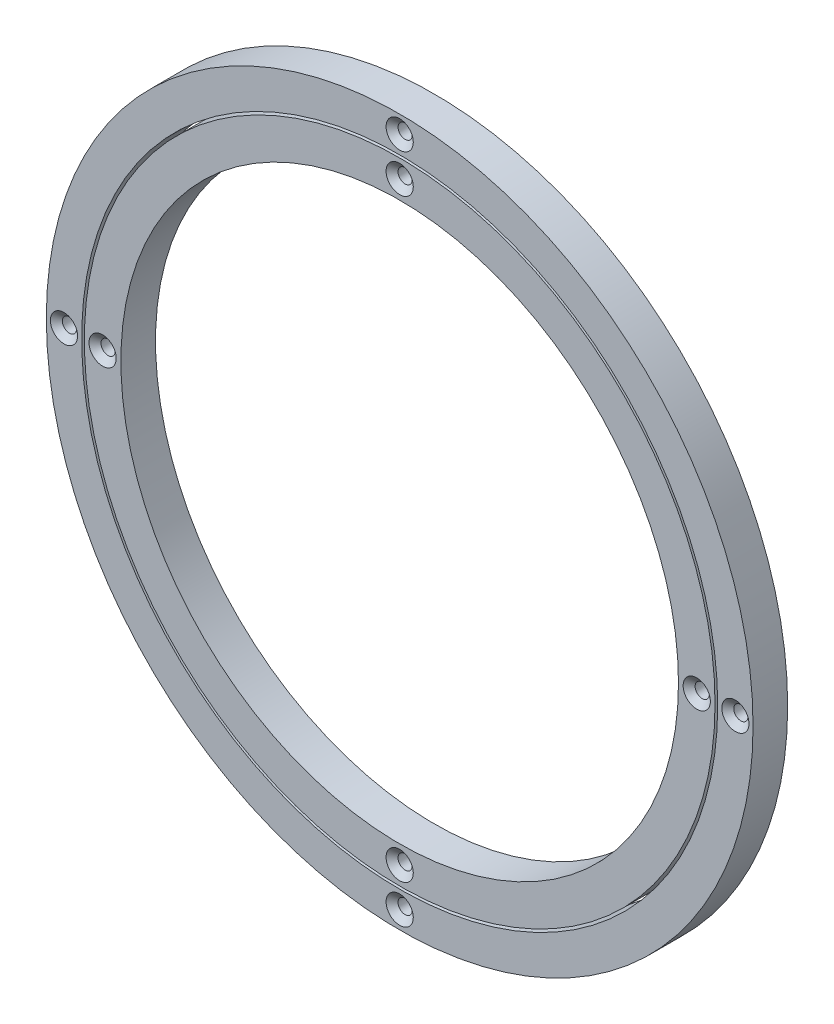
SolidWorks part; units mm, degrees
ref_plane "Front" through (0, 0, 0) normal (0, 0, 1) x (1, 0, 0)
ref_plane "Top" through (0, 0, 0) normal (0, 1, 0) x (1, 0, 0)
ref_plane "Right" through (0, 0, 0) normal (1, 0, 0) x (0, 0, -1)
sketch "Sketch1" plane through (0, 0, 0) normal (0, 0, 1) x (1, 0, 0)
  circle A0 centre (0, 0) radius 127
  circle A1 centre (0, 0) radius 114.3
  circle A2 centre (0, 0) radius 113.3348
  circle A3 centre (0, 0) radius 100.203
  dimension "D1" = 254
  dimension "D2" = 12.7
  dimension "D3" = 0.9652
  dimension "D4" = 13.1318
extrude "Boss-Extrude1" add sketch "Sketch1" along normal blind 12.446 contours A2 A3 | A0 A1
hole_wizard "CSK for #10 Flat Head Machine Screw (100)2" positions "Sketch10" profile "Sketch11" countersink size "#10" standard "ANSI Inch" end condition through all
sketch "Sketch10" plane through (0, 0, 12.446) normal (0, 0, 1) x (1, 0, 0)
  line L0 (0, -127) -> (0, -114.3) construction
  circle A0 centre (0, 0) radius 120.65 construction
  circle A1 centre (0, 0) radius 127 construction
  circle A2 centre (0, 0) radius 114.3 construction
  point P0 (0, -120.65)
  point P5 (-120.65, 0)
  point P7 (0, 120.65)
  point P9 (120.65, 0)
  point P23 (-7.6226, -121.0991)
  point P24 (0, -120.65)
  point P25 (0, 0)
  point P27 (0, -120.65)
  point P28 (0, 0)
  point P29 (0, 0)
  point P30 (0, 0)
  point P31 (0, 0)
  point P32 (0, 0)
  point P33 (0, 0)
  point P34 (120.65, 0)
  point P35 (0, 120.65)
  point P36 (-120.65, 0)
sketch "Sketch11" plane through (0, -120.65, 12.446) normal (1, 0, 0) x (0, -1, 0)
  line L0 (0, 0) -> (0, 12.446)
  line L1 (0, 12.446) -> (2.5527, 12.446)
  line L2 (2.5527, 12.446) -> (2.5527, 1.9608)
  line L3 (2.5527, 1.9608) -> (4.8895, 0)
  line L5 (4.8895, 0) -> (0, 0)
  line L6 (-2.5527, 1.9608) -> (-4.8895, 0) construction
  line L11 (0, -6.35) -> (0, 107.95) construction
  dimension "Thru Hole Dia." = 5.1054
  dimension "Thru Hole Depth" = 12.446
  dimension "Near C'Sink Dia." = 9.779
  dimension "Near C'Sink Angle" = 100
hole_wizard "CSK for #10 Flat Head Machine Screw (100)4" positions "Sketch14" profile "Sketch15" countersink size "#10" standard "ANSI Inch" end condition through all
sketch "Sketch14" plane through (0, 0, 12.446) normal (0, 0, 1) x (1, 0, 0)
  line L0 (-113.3348, 0) -> (-100.203, 0)
  circle A0 centre (0, 0) radius 113.3348 construction
  circle A1 centre (0, 0) radius 100.203 construction
  circle A3 centre (0, 0) radius 106.7689
  point P0 (0, -106.7689)
  point P2 (-106.7689, 0)
  point P4 (0, 106.7689)
  point P6 (106.7689, 0)
  point P8 (-106.7689, 0)
  point P10 (-106.7689, 0)
  point P29 (-106.7689, 0)
  point P30 (-48.7464, 4.8773)
  point P31 (-106.7689, 0)
  point P32 (0, 0)
  point P33 (0, 106.7689)
  point P34 (0, 0)
  point P35 (106.7689, 0)
  point P36 (0, -106.7208)
  point P37 (0, 0)
  point P38 (0, 0)
  point P39 (0, -106.7689)
sketch "Sketch15" plane through (0, -106.7689, 12.446) normal (1, 0, 0) x (0, -1, 0)
  line L0 (0, 0) -> (0, 12.446)
  line L1 (0, 12.446) -> (2.5527, 12.446)
  line L2 (2.5527, 12.446) -> (2.5527, 1.9608)
  line L3 (2.5527, 1.9608) -> (4.8895, 0)
  line L5 (4.8895, 0) -> (0, 0)
  line L6 (-2.5527, 1.9608) -> (-4.8895, 0) construction
  line L11 (0, -6.35) -> (0, 107.95) construction
  dimension "Thru Hole Dia." = 5.1054
  dimension "Thru Hole Depth" = 12.446
  dimension "Near C'Sink Dia." = 9.779
  dimension "Near C'Sink Angle" = 100
